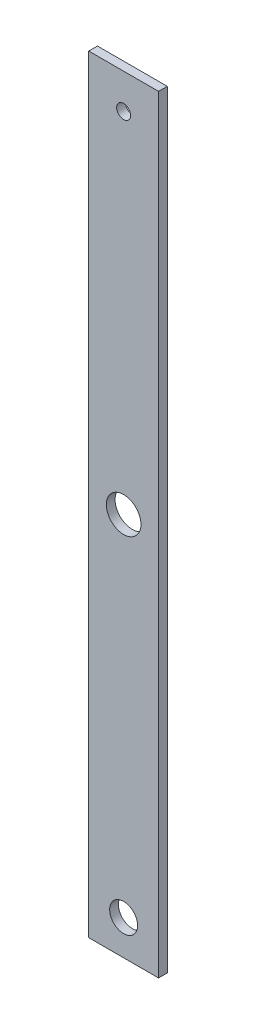
SolidWorks part; units mm, degrees
ref_plane "Front Plane" through (0, 0, 0) normal (0, 0, 1) x (1, 0, 0)
ref_plane "Top Plane" through (0, 0, 0) normal (0, 1, 0) x (1, 0, 0)
ref_plane "Right Plane" through (0, 0, 0) normal (1, 0, 0) x (0, 0, -1)
sketch "Sketch1" plane through (0, 0, 0) normal (0, 0, 1) x (1, 0, 0)
  line L2 (-6.35, 69.85) -> (-6.35, -69.85)
  line L3 (6.35, 69.85) -> (6.35, -69.85)
  line L5 (-6.35, 69.85) -> (6.35, 69.85)
  line L6 (-6.35, -69.85) -> (6.35, -69.85)
  circle A0 centre (0, 0) radius 3.1496
  circle A1 centre (0, 63.5) radius 1.27
  circle A4 centre (0, -63.5) radius 2.54
  point P15 (-6.35, 0)
extrude "Boss-Extrude1" add sketch "Sketch1" along normal blind 1.5875
